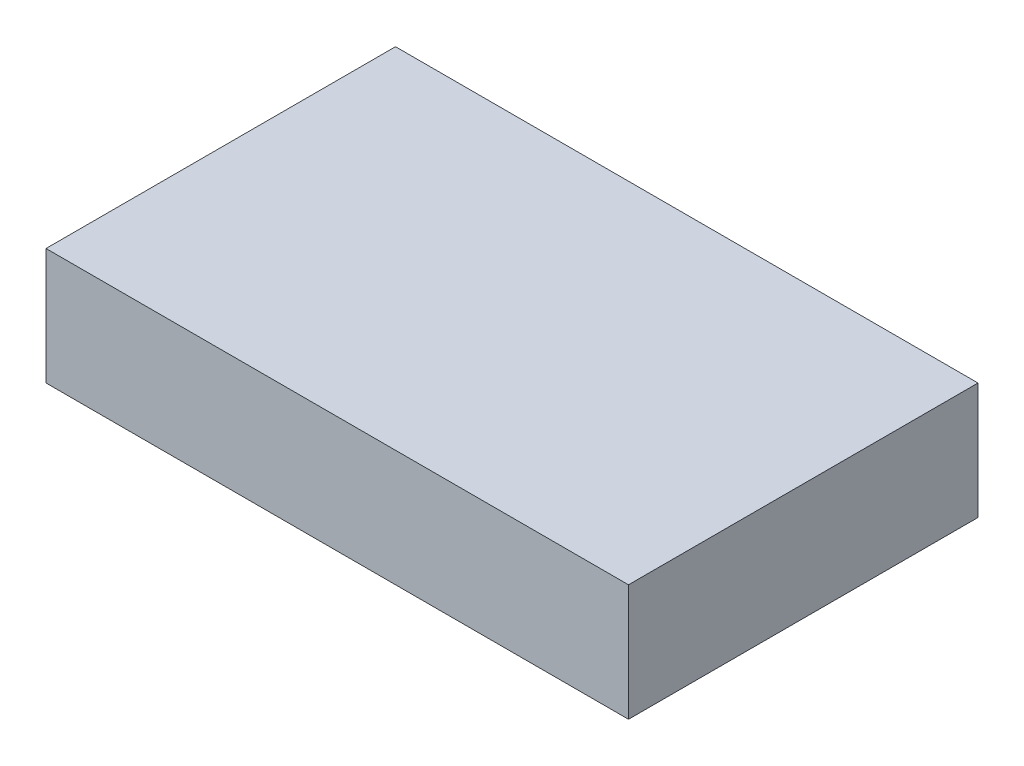
SolidWorks part; units mm, degrees
material "Beton"
ref_plane "Ebene vorne" through (0, 0, 0) normal (0, 0, 1) x (1, 0, 0)
ref_plane "Ebene oben" through (0, 0, 0) normal (0, 1, 0) x (1, 0, 0)
ref_plane "Ebene rechts" through (0, 0, 0) normal (1, 0, 0) x (0, 0, -1)
sketch "Skizze1" plane through (0, 0, 0) normal (0, 1, 0) x (1, 0, 0)
  line L1 (-3276.4415, 1169.1176) -> (1723.5585, 1169.1176)
  line L2 (-3276.4415, 1169.1176) -> (-3276.4415, -1830.8824)
  line L3 (-3276.4415, -1830.8824) -> (1723.5585, -1830.8824)
  line L4 (1723.5585, 1169.1176) -> (1723.5585, -1830.8824)
  dimension "D1" = 5000
  dimension "D2" = 3000
extrude "Aufsatz-Linear austragen1" add sketch "Skizze1" along normal blind 1000
